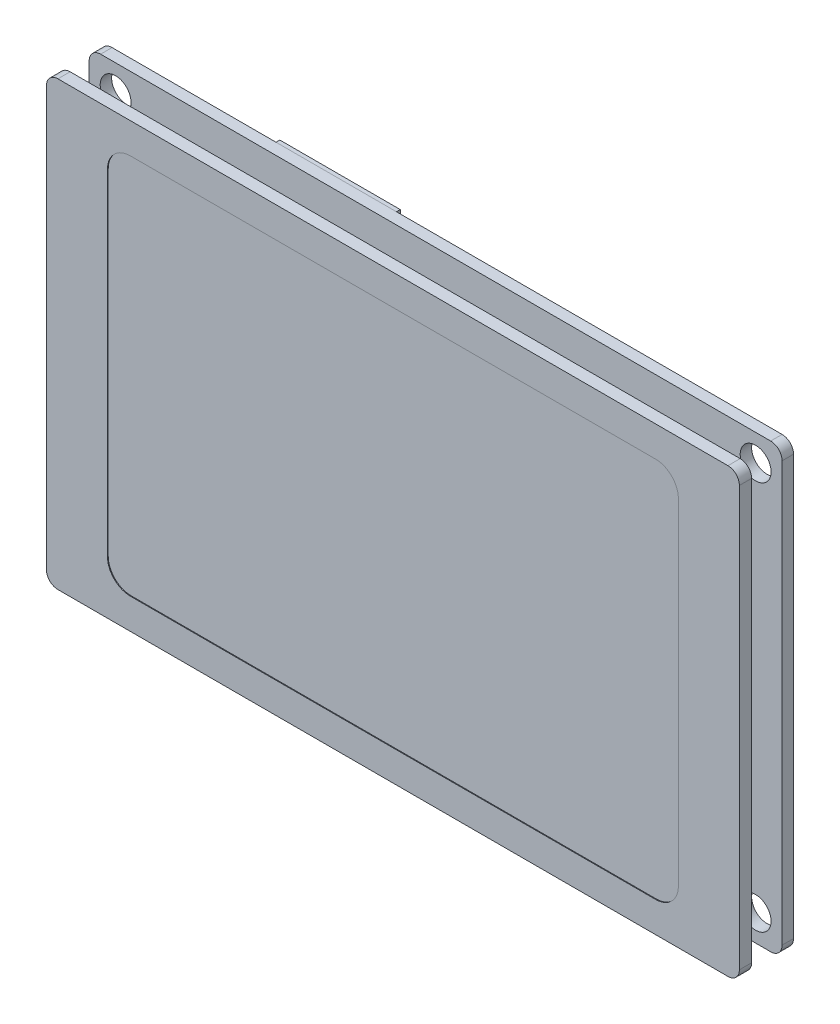
SolidWorks part; units mm, degrees
ref_plane "Front Plane" through (0, 0, 0) normal (0, 0, 1) x (1, 0, 0)
ref_plane "Top Plane" through (0, 0, 0) normal (0, 1, 0) x (1, 0, 0)
ref_plane "Right Plane" through (0, 0, 0) normal (1, 0, 0) x (0, 0, -1)
sketch "Sketch1" plane through (0, 0, 0) normal (0, 0, 1) x (1, 0, 0)
  line L0 (0, 0) -> (-73.8005, 0) construction
  line L1 (-45.435, 29.005) -> (45.435, 29.005)
  line L2 (-45.435, 29.005) -> (-45.435, -29.005)
  line L3 (-45.435, -29.005) -> (45.435, -29.005)
  line L4 (45.435, 29.005) -> (45.435, -29.005)
  line L5 (-45.435, 29.005) -> (45.435, -29.005) construction
  line L6 (-45.435, -29.005) -> (45.435, 29.005) construction
  line L7 (0, 0) -> (0, 42.6738) construction
  circle A0 centre (-41.965, 25.515) radius 2.025
  circle A1 centre (-41.965, -25.515) radius 2.025
  circle A2 centre (41.965, -25.515) radius 2.025
  circle A3 centre (41.965, 25.515) radius 2.025
  point P0 (0, 0)
  dimension "D3" = 4.05
  dimension "D1" = 90.87
  dimension "D2" = 58.01
  dimension "D4" = 3.47
  dimension "D5" = 3.49
extrude "Boss-Extrude1" add sketch "Sketch1" along normal blind 1.5
fillet "Fillet1" radius 1.5 4 edges at (45.435, -29.005, 0.75) (-45.435, -29.005, 0.75) (-45.435, 29.005, 0.75) (45.435, 29.005, 0.75)
sketch "Sketch2" plane through (0, 0, 0) normal (0, 0, -1) x (-1, 0, 0)
  line L0 (45.435, 27.505) -> (45.435, -27.505) construction
  line L1 (37.935, 20.495) -> (42.435, 20.495)
  line L2 (37.935, 20.495) -> (37.935, -20.005)
  line L3 (37.935, -20.005) -> (42.435, -20.005)
  line L4 (42.435, 20.495) -> (42.435, -20.005)
  line L5 (20.435, -21.505) -> (-20.065, -21.505)
  line L6 (20.435, -21.505) -> (20.435, -26.005)
  line L7 (20.435, -26.005) -> (-20.065, -26.005)
  line L8 (-20.065, -21.505) -> (-20.065, -26.005)
  line L9 (43.935, -29.005) -> (-43.935, -29.005) construction
  line L10 (40.435, 19.995) -> (41.935, 19.995)
  line L11 (38.435, 19.995) -> (39.935, 19.995)
  line L12 (38.435, 19.995) -> (38.435, 18.495)
  line L13 (38.435, 18.495) -> (39.935, 18.495)
  line L14 (39.935, 19.995) -> (39.935, 18.495)
  line L19 (40.435, 19.995) -> (40.435, 18.495)
  line L20 (40.435, 18.495) -> (41.935, 18.495)
  line L21 (41.935, 19.995) -> (41.935, 18.495)
  line L22 (40.435, 17.995) -> (41.935, 17.995)
  line L23 (40.435, 17.995) -> (40.435, 16.495)
  line L24 (40.435, 16.495) -> (41.935, 16.495)
  line L25 (41.935, 17.995) -> (41.935, 16.495)
  line L26 (40.435, 15.995) -> (41.935, 15.995)
  line L27 (40.435, 15.995) -> (40.435, 14.495)
  line L28 (40.435, 14.495) -> (41.935, 14.495)
  line L29 (41.935, 15.995) -> (41.935, 14.495)
  line L30 (40.435, 13.995) -> (41.935, 13.995)
  line L31 (40.435, 13.995) -> (40.435, 12.495)
  line L32 (40.435, 12.495) -> (41.935, 12.495)
  line L33 (41.935, 13.995) -> (41.935, 12.495)
  line L34 (40.435, 11.995) -> (41.935, 11.995)
  line L35 (40.435, 11.995) -> (40.435, 10.495)
  line L36 (40.435, 10.495) -> (41.935, 10.495)
  line L37 (41.935, 11.995) -> (41.935, 10.495)
  line L38 (40.435, 9.995) -> (41.935, 9.995)
  line L39 (40.435, 9.995) -> (40.435, 8.495)
  line L40 (40.435, 8.495) -> (41.935, 8.495)
  line L41 (41.935, 9.995) -> (41.935, 8.495)
  line L42 (40.435, 7.995) -> (41.935, 7.995)
  line L43 (40.435, 7.995) -> (40.435, 6.495)
  line L44 (40.435, 6.495) -> (41.935, 6.495)
  line L45 (41.935, 7.995) -> (41.935, 6.495)
  line L46 (40.435, 5.995) -> (41.935, 5.995)
  line L47 (40.435, 5.995) -> (40.435, 4.495)
  line L48 (40.435, 4.495) -> (41.935, 4.495)
  line L49 (41.935, 5.995) -> (41.935, 4.495)
  line L50 (40.435, 3.995) -> (41.935, 3.995)
  line L51 (40.435, 3.995) -> (40.435, 2.495)
  line L52 (40.435, 2.495) -> (41.935, 2.495)
  line L53 (41.935, 3.995) -> (41.935, 2.495)
  line L54 (40.435, 1.995) -> (41.935, 1.995)
  line L55 (40.435, 1.995) -> (40.435, 0.495)
  line L56 (40.435, 0.495) -> (41.935, 0.495)
  line L57 (41.935, 1.995) -> (41.935, 0.495)
  line L58 (40.435, -0.005) -> (41.935, -0.005)
  line L59 (40.435, -0.005) -> (40.435, -1.505)
  line L60 (40.435, -1.505) -> (41.935, -1.505)
  line L61 (41.935, -0.005) -> (41.935, -1.505)
  line L62 (40.435, -2.005) -> (41.935, -2.005)
  line L63 (40.435, -2.005) -> (40.435, -3.505)
  line L64 (40.435, -3.505) -> (41.935, -3.505)
  line L65 (41.935, -2.005) -> (41.935, -3.505)
  line L66 (40.435, -4.005) -> (41.935, -4.005)
  line L67 (40.435, -4.005) -> (40.435, -5.505)
  line L68 (40.435, -5.505) -> (41.935, -5.505)
  line L69 (41.935, -4.005) -> (41.935, -5.505)
  line L70 (40.435, -6.005) -> (41.935, -6.005)
  line L71 (40.435, -6.005) -> (40.435, -7.505)
  line L72 (40.435, -7.505) -> (41.935, -7.505)
  line L73 (41.935, -6.005) -> (41.935, -7.505)
  line L74 (40.435, -8.005) -> (41.935, -8.005)
  line L75 (40.435, -8.005) -> (40.435, -9.505)
  line L76 (40.435, -9.505) -> (41.935, -9.505)
  line L77 (41.935, -8.005) -> (41.935, -9.505)
  line L78 (40.435, -10.005) -> (41.935, -10.005)
  line L79 (40.435, -10.005) -> (40.435, -11.505)
  line L80 (40.435, -11.505) -> (41.935, -11.505)
  line L81 (41.935, -10.005) -> (41.935, -11.505)
  line L82 (40.435, -12.005) -> (41.935, -12.005)
  line L83 (40.435, -12.005) -> (40.435, -13.505)
  line L84 (40.435, -13.505) -> (41.935, -13.505)
  line L85 (41.935, -12.005) -> (41.935, -13.505)
  line L86 (40.435, -14.005) -> (41.935, -14.005)
  line L87 (40.435, -14.005) -> (40.435, -15.505)
  line L88 (40.435, -15.505) -> (41.935, -15.505)
  line L89 (41.935, -14.005) -> (41.935, -15.505)
  line L90 (40.435, -16.005) -> (41.935, -16.005)
  line L91 (40.435, -16.005) -> (40.435, -17.505)
  line L92 (40.435, -17.505) -> (41.935, -17.505)
  line L93 (41.935, -16.005) -> (41.935, -17.505)
  line L94 (40.435, -18.005) -> (41.935, -18.005)
  line L95 (40.435, -18.005) -> (40.435, -19.505)
  line L96 (40.435, -19.505) -> (41.935, -19.505)
  line L97 (41.935, -18.005) -> (41.935, -19.505)
  line L98 (38.435, 17.995) -> (39.935, 17.995)
  line L99 (38.435, 17.995) -> (38.435, 16.495)
  line L100 (38.435, 16.495) -> (39.935, 16.495)
  line L101 (39.935, 17.995) -> (39.935, 16.495)
  line L102 (38.435, 15.995) -> (39.935, 15.995)
  line L103 (38.435, 15.995) -> (38.435, 14.495)
  line L104 (38.435, 14.495) -> (39.935, 14.495)
  line L105 (39.935, 15.995) -> (39.935, 14.495)
  line L106 (38.435, 13.995) -> (39.935, 13.995)
  line L107 (38.435, 13.995) -> (38.435, 12.495)
  line L108 (38.435, 12.495) -> (39.935, 12.495)
  line L109 (39.935, 13.995) -> (39.935, 12.495)
  line L110 (38.435, 11.995) -> (39.935, 11.995)
  line L111 (38.435, 11.995) -> (38.435, 10.495)
  line L112 (38.435, 10.495) -> (39.935, 10.495)
  line L113 (39.935, 11.995) -> (39.935, 10.495)
  line L114 (38.435, 9.995) -> (39.935, 9.995)
  line L115 (38.435, 9.995) -> (38.435, 8.495)
  line L116 (38.435, 8.495) -> (39.935, 8.495)
  line L117 (39.935, 9.995) -> (39.935, 8.495)
  line L118 (38.435, 7.995) -> (39.935, 7.995)
  line L119 (38.435, 7.995) -> (38.435, 6.495)
  line L120 (38.435, 6.495) -> (39.935, 6.495)
  line L121 (39.935, 7.995) -> (39.935, 6.495)
  line L122 (38.435, 5.995) -> (39.935, 5.995)
  line L123 (38.435, 5.995) -> (38.435, 4.495)
  line L124 (38.435, 4.495) -> (39.935, 4.495)
  line L125 (39.935, 5.995) -> (39.935, 4.495)
  line L126 (38.435, 3.995) -> (39.935, 3.995)
  line L127 (38.435, 3.995) -> (38.435, 2.495)
  line L128 (38.435, 2.495) -> (39.935, 2.495)
  line L129 (39.935, 3.995) -> (39.935, 2.495)
  line L130 (38.435, 1.995) -> (39.935, 1.995)
  line L131 (38.435, 1.995) -> (38.435, 0.495)
  line L132 (38.435, 0.495) -> (39.935, 0.495)
  line L133 (39.935, 1.995) -> (39.935, 0.495)
  line L134 (38.435, -0.005) -> (39.935, -0.005)
  line L135 (38.435, -0.005) -> (38.435, -1.505)
  line L136 (38.435, -1.505) -> (39.935, -1.505)
  line L137 (39.935, -0.005) -> (39.935, -1.505)
  line L138 (38.435, -2.005) -> (39.935, -2.005)
  line L139 (38.435, -2.005) -> (38.435, -3.505)
  line L140 (38.435, -3.505) -> (39.935, -3.505)
  line L141 (39.935, -2.005) -> (39.935, -3.505)
  line L142 (38.435, -4.005) -> (39.935, -4.005)
  line L143 (38.435, -4.005) -> (38.435, -5.505)
  line L144 (38.435, -5.505) -> (39.935, -5.505)
  line L145 (39.935, -4.005) -> (39.935, -5.505)
  line L146 (38.435, -6.005) -> (39.935, -6.005)
  line L147 (38.435, -6.005) -> (38.435, -7.505)
  line L148 (38.435, -7.505) -> (39.935, -7.505)
  line L149 (39.935, -6.005) -> (39.935, -7.505)
  line L150 (38.435, -8.005) -> (39.935, -8.005)
  line L151 (38.435, -8.005) -> (38.435, -9.505)
  line L152 (38.435, -9.505) -> (39.935, -9.505)
  line L153 (39.935, -8.005) -> (39.935, -9.505)
  line L154 (38.435, -10.005) -> (39.935, -10.005)
  line L155 (38.435, -10.005) -> (38.435, -11.505)
  line L156 (38.435, -11.505) -> (39.935, -11.505)
  line L157 (39.935, -10.005) -> (39.935, -11.505)
  line L158 (38.435, -12.005) -> (39.935, -12.005)
  line L159 (38.435, -12.005) -> (38.435, -13.505)
  line L160 (38.435, -13.505) -> (39.935, -13.505)
  line L161 (39.935, -12.005) -> (39.935, -13.505)
  line L162 (38.435, -14.005) -> (39.935, -14.005)
  line L163 (38.435, -14.005) -> (38.435, -15.505)
  line L164 (38.435, -15.505) -> (39.935, -15.505)
  line L165 (39.935, -14.005) -> (39.935, -15.505)
  line L166 (38.435, -16.005) -> (39.935, -16.005)
  line L167 (38.435, -16.005) -> (38.435, -17.505)
  line L168 (38.435, -17.505) -> (39.935, -17.505)
  line L169 (39.935, -16.005) -> (39.935, -17.505)
  line L170 (38.435, -18.005) -> (39.935, -18.005)
  line L171 (38.435, -18.005) -> (38.435, -19.505)
  line L172 (38.435, -19.505) -> (39.935, -19.505)
  line L173 (39.935, -18.005) -> (39.935, -19.505)
  line L174 (-17.565, -23.505) -> (-16.065, -23.505)
  line L175 (-19.565, -22.005) -> (-18.065, -22.005)
  line L176 (-19.565, -22.005) -> (-19.565, -23.505)
  line L177 (-19.565, -23.505) -> (-18.065, -23.505)
  line L178 (-18.065, -22.005) -> (-18.065, -23.505)
  line L179 (-17.565, -22.005) -> (-17.565, -23.505)
  line L180 (-17.565, -22.005) -> (-16.065, -22.005)
  line L181 (-16.065, -22.005) -> (-16.065, -23.505)
  line L182 (-15.565, -23.505) -> (-14.065, -23.505)
  line L183 (-15.565, -22.005) -> (-15.565, -23.505)
  line L184 (-15.565, -22.005) -> (-14.065, -22.005)
  line L185 (-14.065, -22.005) -> (-14.065, -23.505)
  line L186 (-13.565, -23.505) -> (-12.065, -23.505)
  line L187 (-13.565, -22.005) -> (-13.565, -23.505)
  line L188 (-13.565, -22.005) -> (-12.065, -22.005)
  line L189 (-12.065, -22.005) -> (-12.065, -23.505)
  line L190 (-11.565, -23.505) -> (-10.065, -23.505)
  line L191 (-11.565, -22.005) -> (-11.565, -23.505)
  line L192 (-11.565, -22.005) -> (-10.065, -22.005)
  line L193 (-10.065, -22.005) -> (-10.065, -23.505)
  line L194 (-9.565, -23.505) -> (-8.065, -23.505)
  line L195 (-9.565, -22.005) -> (-9.565, -23.505)
  line L196 (-9.565, -22.005) -> (-8.065, -22.005)
  line L197 (-8.065, -22.005) -> (-8.065, -23.505)
  line L198 (-7.565, -23.505) -> (-6.065, -23.505)
  line L199 (-7.565, -22.005) -> (-7.565, -23.505)
  line L200 (-7.565, -22.005) -> (-6.065, -22.005)
  line L201 (-6.065, -22.005) -> (-6.065, -23.505)
  line L202 (-5.565, -23.505) -> (-4.065, -23.505)
  line L203 (-5.565, -22.005) -> (-5.565, -23.505)
  line L204 (-5.565, -22.005) -> (-4.065, -22.005)
  line L205 (-4.065, -22.005) -> (-4.065, -23.505)
  line L206 (-3.565, -23.505) -> (-2.065, -23.505)
  line L207 (-3.565, -22.005) -> (-3.565, -23.505)
  line L208 (-3.565, -22.005) -> (-2.065, -22.005)
  line L209 (-2.065, -22.005) -> (-2.065, -23.505)
  line L210 (-1.565, -23.505) -> (-0.065, -23.505)
  line L211 (-1.565, -22.005) -> (-1.565, -23.505)
  line L212 (-1.565, -22.005) -> (-0.065, -22.005)
  line L213 (-0.065, -22.005) -> (-0.065, -23.505)
  line L214 (0.435, -23.505) -> (1.935, -23.505)
  line L215 (0.435, -22.005) -> (0.435, -23.505)
  line L216 (0.435, -22.005) -> (1.935, -22.005)
  line L217 (1.935, -22.005) -> (1.935, -23.505)
  line L218 (2.435, -23.505) -> (3.935, -23.505)
  line L219 (2.435, -22.005) -> (2.435, -23.505)
  line L220 (2.435, -22.005) -> (3.935, -22.005)
  line L221 (3.935, -22.005) -> (3.935, -23.505)
  line L222 (4.435, -23.505) -> (5.935, -23.505)
  line L223 (4.435, -22.005) -> (4.435, -23.505)
  line L224 (4.435, -22.005) -> (5.935, -22.005)
  line L225 (5.935, -22.005) -> (5.935, -23.505)
  line L226 (6.435, -23.505) -> (7.935, -23.505)
  line L227 (6.435, -22.005) -> (6.435, -23.505)
  line L228 (6.435, -22.005) -> (7.935, -22.005)
  line L229 (7.935, -22.005) -> (7.935, -23.505)
  line L230 (8.435, -23.505) -> (9.935, -23.505)
  line L231 (8.435, -22.005) -> (8.435, -23.505)
  line L232 (8.435, -22.005) -> (9.935, -22.005)
  line L233 (9.935, -22.005) -> (9.935, -23.505)
  line L234 (10.435, -23.505) -> (11.935, -23.505)
  line L235 (10.435, -22.005) -> (10.435, -23.505)
  line L236 (10.435, -22.005) -> (11.935, -22.005)
  line L237 (11.935, -22.005) -> (11.935, -23.505)
  line L238 (12.435, -23.505) -> (13.935, -23.505)
  line L239 (12.435, -22.005) -> (12.435, -23.505)
  line L240 (12.435, -22.005) -> (13.935, -22.005)
  line L241 (13.935, -22.005) -> (13.935, -23.505)
  line L242 (14.435, -23.505) -> (15.935, -23.505)
  line L243 (14.435, -22.005) -> (14.435, -23.505)
  line L244 (14.435, -22.005) -> (15.935, -22.005)
  line L245 (15.935, -22.005) -> (15.935, -23.505)
  line L246 (16.435, -23.505) -> (17.935, -23.505)
  line L247 (16.435, -22.005) -> (16.435, -23.505)
  line L248 (16.435, -22.005) -> (17.935, -22.005)
  line L249 (17.935, -22.005) -> (17.935, -23.505)
  line L250 (18.435, -23.505) -> (19.935, -23.505)
  line L251 (18.435, -22.005) -> (18.435, -23.505)
  line L252 (18.435, -22.005) -> (19.935, -22.005)
  line L253 (19.935, -22.005) -> (19.935, -23.505)
  line L254 (-17.565, -25.505) -> (-16.065, -25.505)
  line L255 (-17.565, -24.005) -> (-17.565, -25.505)
  line L256 (-17.565, -24.005) -> (-16.065, -24.005)
  line L257 (-16.065, -24.005) -> (-16.065, -25.505)
  line L258 (-15.565, -25.505) -> (-14.065, -25.505)
  line L259 (-15.565, -24.005) -> (-15.565, -25.505)
  line L260 (-15.565, -24.005) -> (-14.065, -24.005)
  line L261 (-14.065, -24.005) -> (-14.065, -25.505)
  line L262 (-13.565, -25.505) -> (-12.065, -25.505)
  line L263 (-13.565, -24.005) -> (-13.565, -25.505)
  line L264 (-13.565, -24.005) -> (-12.065, -24.005)
  line L265 (-12.065, -24.005) -> (-12.065, -25.505)
  line L266 (-11.565, -25.505) -> (-10.065, -25.505)
  line L267 (-11.565, -24.005) -> (-11.565, -25.505)
  line L268 (-11.565, -24.005) -> (-10.065, -24.005)
  line L269 (-10.065, -24.005) -> (-10.065, -25.505)
  line L270 (-9.565, -25.505) -> (-8.065, -25.505)
  line L271 (-9.565, -24.005) -> (-9.565, -25.505)
  line L272 (-9.565, -24.005) -> (-8.065, -24.005)
  line L273 (-8.065, -24.005) -> (-8.065, -25.505)
  line L274 (-7.565, -25.505) -> (-6.065, -25.505)
  line L275 (-7.565, -24.005) -> (-7.565, -25.505)
  line L276 (-7.565, -24.005) -> (-6.065, -24.005)
  line L277 (-6.065, -24.005) -> (-6.065, -25.505)
  line L278 (-5.565, -25.505) -> (-4.065, -25.505)
  line L279 (-5.565, -24.005) -> (-5.565, -25.505)
  line L280 (-5.565, -24.005) -> (-4.065, -24.005)
  line L281 (-4.065, -24.005) -> (-4.065, -25.505)
  line L282 (-3.565, -25.505) -> (-2.065, -25.505)
  line L283 (-3.565, -24.005) -> (-3.565, -25.505)
  line L284 (-3.565, -24.005) -> (-2.065, -24.005)
  line L285 (-2.065, -24.005) -> (-2.065, -25.505)
  line L286 (-1.565, -25.505) -> (-0.065, -25.505)
  line L287 (-1.565, -24.005) -> (-1.565, -25.505)
  line L288 (-1.565, -24.005) -> (-0.065, -24.005)
  line L289 (-0.065, -24.005) -> (-0.065, -25.505)
  line L290 (0.435, -25.505) -> (1.935, -25.505)
  line L291 (0.435, -24.005) -> (0.435, -25.505)
  line L292 (0.435, -24.005) -> (1.935, -24.005)
  line L293 (1.935, -24.005) -> (1.935, -25.505)
  line L294 (2.435, -25.505) -> (3.935, -25.505)
  line L295 (2.435, -24.005) -> (2.435, -25.505)
  line L296 (2.435, -24.005) -> (3.935, -24.005)
  line L297 (3.935, -24.005) -> (3.935, -25.505)
  line L298 (4.435, -25.505) -> (5.935, -25.505)
  line L299 (4.435, -24.005) -> (4.435, -25.505)
  line L300 (4.435, -24.005) -> (5.935, -24.005)
  line L301 (5.935, -24.005) -> (5.935, -25.505)
  line L302 (6.435, -25.505) -> (7.935, -25.505)
  line L303 (6.435, -24.005) -> (6.435, -25.505)
  line L304 (6.435, -24.005) -> (7.935, -24.005)
  line L305 (7.935, -24.005) -> (7.935, -25.505)
  line L306 (8.435, -25.505) -> (9.935, -25.505)
  line L307 (8.435, -24.005) -> (8.435, -25.505)
  line L308 (8.435, -24.005) -> (9.935, -24.005)
  line L309 (9.935, -24.005) -> (9.935, -25.505)
  line L310 (10.435, -25.505) -> (11.935, -25.505)
  line L311 (10.435, -24.005) -> (10.435, -25.505)
  line L312 (10.435, -24.005) -> (11.935, -24.005)
  line L313 (11.935, -24.005) -> (11.935, -25.505)
  line L314 (12.435, -25.505) -> (13.935, -25.505)
  line L315 (12.435, -24.005) -> (12.435, -25.505)
  line L316 (12.435, -24.005) -> (13.935, -24.005)
  line L317 (13.935, -24.005) -> (13.935, -25.505)
  line L318 (14.435, -25.505) -> (15.935, -25.505)
  line L319 (14.435, -24.005) -> (14.435, -25.505)
  line L320 (14.435, -24.005) -> (15.935, -24.005)
  line L321 (15.935, -24.005) -> (15.935, -25.505)
  line L322 (16.435, -25.505) -> (17.935, -25.505)
  line L323 (16.435, -24.005) -> (16.435, -25.505)
  line L324 (16.435, -24.005) -> (17.935, -24.005)
  line L325 (17.935, -24.005) -> (17.935, -25.505)
  line L326 (18.435, -25.505) -> (19.935, -25.505)
  line L327 (18.435, -24.005) -> (18.435, -25.505)
  line L328 (18.435, -24.005) -> (19.935, -24.005)
  line L329 (19.935, -24.005) -> (19.935, -25.505)
  line L330 (-19.565, -25.505) -> (-18.065, -25.505)
  line L331 (-19.565, -24.005) -> (-19.565, -25.505)
  line L332 (-19.565, -24.005) -> (-18.065, -24.005)
  line L333 (-18.065, -24.005) -> (-18.065, -25.505)
  dimension "D1" = 4.5
  dimension "D2" = 40.5
  dimension "D3" = 40.5
  dimension "D4" = 4.5
  dimension "D5" = 3
  dimension "D6" = 9
  dimension "D7" = 3
  dimension "D8" = 25
  dimension "D9" = 1.5
  dimension "D10" = 1.5
  dimension "D11" = 0.5
  dimension "D12" = 0.5
  dimension "D13" = 0.5
  dimension "D14" = 0.5
  dimension "D15" = 2
  dimension "D16" = 1.5
  dimension "D18" = 1.5
  dimension "D17" = 20
  dimension "D19" = 20
  dimension "D20" = 2
extrude "Boss-Extrude2" add sketch "Sketch2" along normal blind 5 separate body
sketch "Sketch3" plane through (0, 0, 0) normal (0, 0, -1) x (-1, 0, 0)
  line L0 (-43.935, 29.005) -> (43.935, 29.005) construction
  line L1 (6.635, 29.005) -> (22.435, 29.005)
  line L2 (6.635, 29.005) -> (6.635, -2.295)
  line L3 (6.635, -2.295) -> (22.435, -2.295)
  line L4 (22.435, 29.005) -> (22.435, -2.295)
  line L5 (45.435, 27.505) -> (45.435, -27.505) construction
  dimension "D1" = 15.8
  dimension "D2" = 31.3
  dimension "D3" = 23
extrude "Boss-Extrude3" add sketch "Sketch3" along normal blind 0.5 separate body
sketch "Sketch4" plane through (0, 0, -0.5) normal (0, 0, -1) x (-1, 0, 0)
  line L0 (6.635, -2.295) -> (22.435, -2.295)
  line L1 (22.435, -2.295) -> (22.435, 29.005) construction
  line L2 (6.635, -2.295) -> (22.435, -2.295) construction
  line L3 (22.435, -2.295) -> (22.435, 17.705)
  line L4 (22.435, 17.705) -> (15.935, 17.705)
  line L5 (15.935, 17.705) -> (15.935, 21.705)
  line L6 (15.935, 21.705) -> (6.635, 21.705)
  line L7 (6.635, 29.005) -> (6.635, -2.295) construction
  line L8 (6.635, 21.705) -> (6.635, -2.295)
  dimension "D1" = 20
  dimension "D2" = 24
  dimension "D3" = 6.5
extrude "Boss-Extrude4" add sketch "Sketch4" along normal blind 2.7 separate body
sketch "Sketch5" plane through (0, 0, 1.5) normal (0, 0, 1) x (1, 0, 0)
  line L1 (-40, 22.5) -> (40, 22.5)
  line L2 (-40, 22.5) -> (-40, -22.5)
  line L3 (-40, -22.5) -> (40, -22.5)
  line L4 (40, 22.5) -> (40, -22.5)
  line L5 (-40, 22.5) -> (40, -22.5) construction
  line L6 (-40, -22.5) -> (40, 22.5) construction
  point P0 (0, 0)
  dimension "D1" = 80
  dimension "D2" = 45
extrude "Boss-Extrude5" add sketch "Sketch5" along normal blind 4 separate body
sketch "Sketch6" plane through (0, 0, 5.5) normal (0, 0, 1) x (1, 0, 0)
  line L0 (-43.935, -29.005) -> (43.935, -29.005) construction
  line L1 (45.435, -27.505) -> (45.435, 27.505) construction
  line L2 (-45.435, 27.505) -> (-45.435, -27.505) construction
  line L3 (43.935, 29.005) -> (-43.935, 29.005) construction
  line L4 (-43.935, -29.005) -> (43.935, -29.005)
  line L5 (45.435, -27.505) -> (45.435, 27.505)
  line L6 (-45.435, 27.505) -> (-45.435, -27.505)
  line L7 (43.935, 29.005) -> (-43.935, 29.005)
  arc A0 (-45.435, -27.505) -> (-43.935, -29.005) centre (-43.935, -27.505) ccw construction
  arc A1 (43.935, -29.005) -> (45.435, -27.505) centre (43.935, -27.505) ccw construction
  arc A2 (45.435, 27.505) -> (43.935, 29.005) centre (43.935, 27.505) ccw construction
  arc A3 (-43.935, 29.005) -> (-45.435, 27.505) centre (-43.935, 27.505) ccw construction
  arc A4 (-45.435, -27.505) -> (-43.935, -29.005) centre (-43.935, -27.505) ccw
  arc A5 (43.935, -29.005) -> (45.435, -27.505) centre (43.935, -27.505) ccw
  arc A6 (45.435, 27.505) -> (43.935, 29.005) centre (43.935, 27.505) ccw
  arc A7 (-43.935, 29.005) -> (-45.435, 27.505) centre (-43.935, 27.505) ccw
extrude "Boss-Extrude6" add sketch "Sketch6" along normal blind 1.6 separate body
sketch "Sketch7" plane through (0, 0, 7.1) normal (0, 0, 1) x (1, 0, 0)
  line L5 (-43.935, -29.005) -> (43.935, -29.005) construction
  line L6 (-34.435, 25.005) -> (34.435, 25.005)
  line L7 (-37.435, 22.005) -> (-37.435, -22.005)
  line L12 (-34.435, -25.005) -> (34.435, -25.005)
  line L13 (37.435, 22.005) -> (37.435, -22.005)
  line L14 (-37.435, 25.005) -> (37.435, -25.005) construction
  line L15 (-37.435, -25.005) -> (37.435, 25.005) construction
  line L16 (45.435, -27.505) -> (45.435, 27.505) construction
  arc A12 (-37.435, -22.005) -> (-34.435, -25.005) centre (-34.435, -22.005) ccw
  arc A13 (34.435, -25.005) -> (37.435, -22.005) centre (34.435, -22.005) ccw
  arc A14 (34.435, 25.005) -> (37.435, 22.005) centre (34.435, 22.005) cw
  arc A15 (-34.435, 25.005) -> (-37.435, 22.005) centre (-34.435, 22.005) ccw
  point P0 (0, 0)
  dimension "D3" = 3
  dimension "D1" = 4
  dimension "D2" = 8
extrude "Cut-Extrude1" cut sketch "Sketch7" against normal blind 0.1
